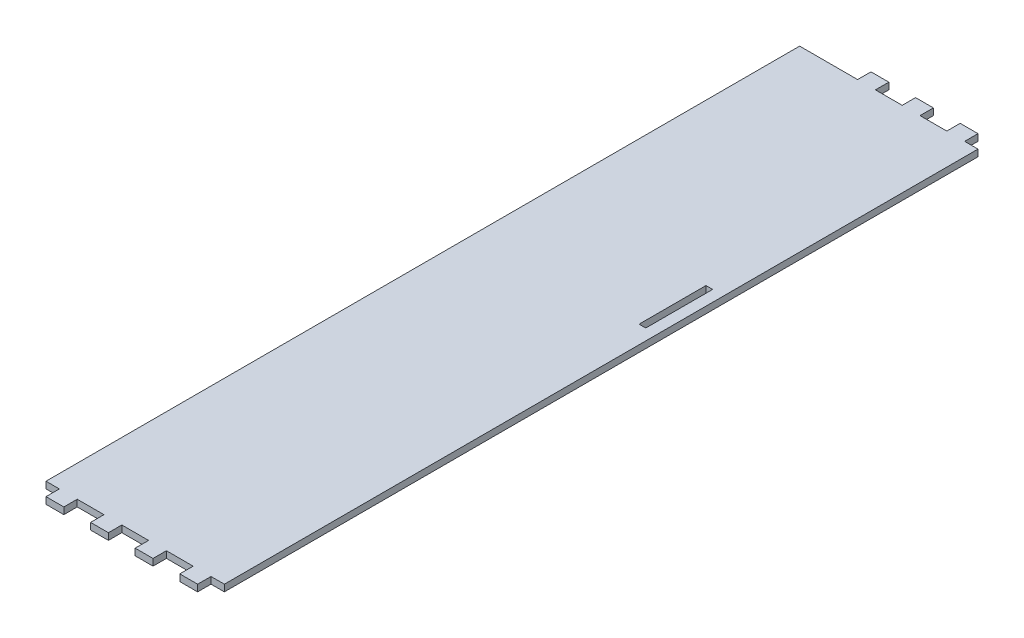
SolidWorks part; units mm, degrees
ref_plane "Plan de face" through (0, 0, 0) normal (0, 0, 1) x (1, 0, 0)
ref_plane "Plan de dessus" through (0, 0, 0) normal (0, 1, 0) x (1, 0, 0)
ref_plane "Plan de droite" through (0, 0, 0) normal (1, 0, 0) x (0, 0, -1)
sketch "Esquisse1" plane through (0, 0, 0) normal (0, 0, 1) x (1, 0, 0)
  line L1 (0, 0) -> (80, 0)
  line L2 (0, 0) -> (0, 3)
  line L3 (0, 3) -> (80, 3)
  line L4 (80, 0) -> (80, 3)
  dimension "D1" = 3
  dimension "D2" = 80
extrude "Boss.-Extru.1" add sketch "Esquisse1" along normal blind 338
sketch "Esquisse2" plane through (0, 0, 0) normal (0, -1, 0) x (1, 0, 0)
  line L4 (74, 50) -> (66, 50)
  line L5 (74, 50) -> (74, 56)
  line L6 (74, 56) -> (66, 56)
  line L7 (66, 50) -> (66, 56)
  line L8 (54, 50) -> (46, 50)
  line L9 (54, 50) -> (54, 56)
  line L10 (54, 56) -> (46, 56)
  line L11 (46, 50) -> (46, 56)
  line L12 (34, 50) -> (26, 50)
  line L13 (34, 50) -> (34, 56)
  line L14 (34, 56) -> (26, 56)
  line L15 (26, 50) -> (26, 56)
  line L16 (14, 50) -> (6, 50)
  line L17 (14, 50) -> (14, 56)
  line L18 (14, 56) -> (6, 56)
  line L19 (6, 50) -> (6, 56)
  line L20 (0, 338) -> (0, 0) construction
  line L21 (0, 0) -> (80, 0) construction
  line L22 (0, 56) -> (80, 56)
  line L23 (80, 338) -> (80, 0) construction
  line L24 (80, 56) -> (80, 50)
  line L25 (80, 50) -> (0, 50)
  line L26 (0, 50) -> (0, 56)
  dimension "D1" = 12
  dimension "D2" = 12
  dimension "D3" = 12
  dimension "D5" = 6
  dimension "D6" = 6
  dimension "D7" = 8
  dimension "D8" = 50
extrude "Enlèv. mat.-Extru.1" [suppressed] cut sketch "Esquisse2" against normal blind 6
ref_plane "Plan1" through (0, 0, 169) normal (0, 0, -1) x (-1, 0, 0)
sketch "Esquisse3" plane through (0, 0, 0) normal (0, 0, -1) x (-1, 0, 0)
  line L0 (0, 0) -> (-80, 0) construction
  line L1 (-6, 0) -> (-14, 0)
  line L2 (-6, 0) -> (-6, 3)
  line L3 (-6, 3) -> (-14, 3)
  line L4 (-14, 0) -> (-14, 3)
  line L5 (-80, 3) -> (0, 3) construction
  line L6 (-26, 0) -> (-34, 0)
  line L7 (-26, 0) -> (-26, 3)
  line L8 (-26, 3) -> (-34, 3)
  line L9 (-34, 0) -> (-34, 3)
  line L10 (-46, 0) -> (-54, 0)
  line L11 (-46, 0) -> (-46, 3)
  line L12 (-46, 3) -> (-54, 3)
  line L13 (-54, 0) -> (-54, 3)
  line L14 (-66, 0) -> (-74, 0)
  line L15 (-66, 0) -> (-66, 3)
  line L16 (-66, 3) -> (-74, 3)
  line L17 (-74, 0) -> (-74, 3)
  line L22 (0, 3) -> (0, 0) construction
  line L23 (-86, 0) -> (-94, 0) [skipped]
  line L24 (-86, 0) -> (-86, 3) [skipped]
  line L25 (-86, 3) -> (-94, 3) [skipped]
  line L26 (-94, 0) -> (-94, 3) [skipped]
  dimension "D1" = 8
  dimension "D2" = 5
  dimension "D3" = 6
extrude "Boss.-Extru.2" add sketch "Esquisse3" along normal blind 6
mirror "Symétrie1" about plane through (0, 0, 169) normal (0, 0, -1) of "Boss.-Extru.2"
sketch "Esquisse4" plane through (0, 0, 0) normal (0, -1, 0) x (1, 0, 0)
  line L0 (14, 0) -> (14, -6)
  line L1 (14, 0) -> (6, 0)
  line L2 (14, -6) -> (6, -6)
  line L3 (6, 0) -> (6, -6)
  line L4 (14, -6) -> (6, -6) construction
  line L5 (6, -6) -> (6, 0) construction
extrude "Enlèv. mat.-Extru.2" cut sketch "Esquisse4" against normal blind 6
sketch "Esquisse5" plane through (0, 0, 0) normal (0, -1, 0) x (1, 0, 0)
  line L1 (72, 144) -> (75, 144)
  line L2 (72, 144) -> (72, 114)
  line L3 (72, 114) -> (75, 114)
  line L4 (75, 144) -> (75, 114)
extrude "Enlèv. mat.-Extru.3" cut sketch "Esquisse5" against normal blind 3
